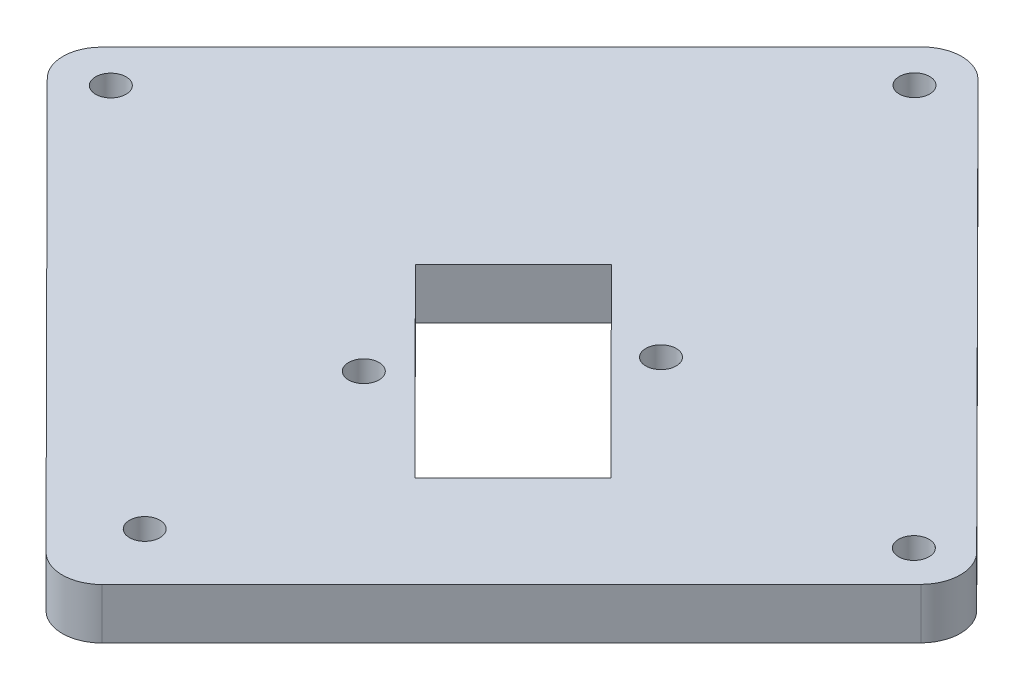
SolidWorks part; units mm, degrees
ref_plane "Front Plane" through (0, 0, 0) normal (0, 0, 1) x (1, 0, 0)
ref_plane "Top Plane" through (0, 0, 0) normal (0, 1, 0) x (1, 0, 0)
ref_plane "Right Plane" through (0, 0, 0) normal (1, 0, 0) x (0, 0, -1)
sketch "Sketch1" plane through (0, 0, 0) normal (0, 1, 0) x (1, 0, 0)
  line L0 (8.317, -9.341) -> (-3.2366, 2.2479)
  line L1 (-3.2366, 2.2479) -> (2.8992, 8.3877)
  line L2 (2.8992, 8.3877) -> (14.453, -3.2014)
  line L3 (14.453, -3.2014) -> (8.317, -9.341)
  line L4 (0.8361, 29.9147) -> (-24.9169, 4.1391)
  line L5 (-24.8042, 0.7619) -> (0.802, -24.9225)
  line L6 (2.6704, 28.5385) -> (2.6704, 26.6517) construction
  line L7 (4.2961, -24.9246) -> (29.9338, 0.7279)
  line L8 (30.0224, 4.1369) -> (4.3298, 29.9125)
  line L9 (2.6704, 27.5951) -> (1.7124, 27.5951) construction
  line L10 (-21.8117, 3.0844) -> (-23.1436, 3.0851) construction
  line L11 (-23.1445, 1.7506) -> (-21.8127, 1.7499) construction
  line L12 (-22.4777, 3.0847) -> (-22.4786, 1.7503) construction
  line L13 (1.9646, -19.901) -> (3.2965, -19.9019) construction
  line L14 (1.9636, -21.2353) -> (3.2957, -21.2361) construction
  line L15 (2.6305, -19.9014) -> (2.6296, -21.2357) construction
  line L16 (0.2697, -4.4869) -> (1.6016, -4.4878) construction
  line L17 (0.2688, -5.8212) -> (1.6007, -5.8222) construction
  line L18 (0.9356, -4.4874) -> (0.9347, -5.8217) construction
  line L19 (8.8139, 4.2428) -> (10.1459, 4.242) construction
  line L20 (10.1459, 4.242) -> (10.1196, 4.2497) construction
  line L21 (8.8147, 5.5771) -> (10.1468, 5.5762) construction
  line L22 (9.4807, 5.5767) -> (9.4799, 4.2424) construction
  line L23 (27.0813, 3.1247) -> (28.4132, 3.1238) construction
  line L24 (27.0804, 1.7902) -> (28.4125, 1.7894) construction
  line L25 (27.7473, 3.1242) -> (27.7464, 1.7898) construction
  arc A0 (-24.9169, 4.1391) -> (-24.8042, 0.7619) centre (-23.1718, 2.5069) ccw
  arc A1 (0.802, -24.9225) -> (4.2961, -24.9246) centre (2.5501, -23.1797) ccw
  arc A2 (29.9338, 0.7279) -> (30.0224, 4.1369) centre (28.1816, 2.4791) ccw
  arc A3 (4.3298, 29.9125) -> (0.8361, 29.9147) centre (2.5819, 28.1699) ccw
  circle A4 centre (2.6704, 27.5951) radius 0.9525
  circle A5 centre (-22.4781, 2.4175) radius 0.9525
  circle A6 centre (0.9352, -5.1545) radius 0.9525
  circle A7 centre (9.4803, 4.9095) radius 0.9525
  circle A8 centre (2.6301, -20.5685) radius 0.9525
  circle A9 centre (27.7469, 2.4791) radius 0.9525
  dimension "D1" = 1.905
extrude "Boss-Extrude1" add sketch "Sketch1" along normal blind 3.175
